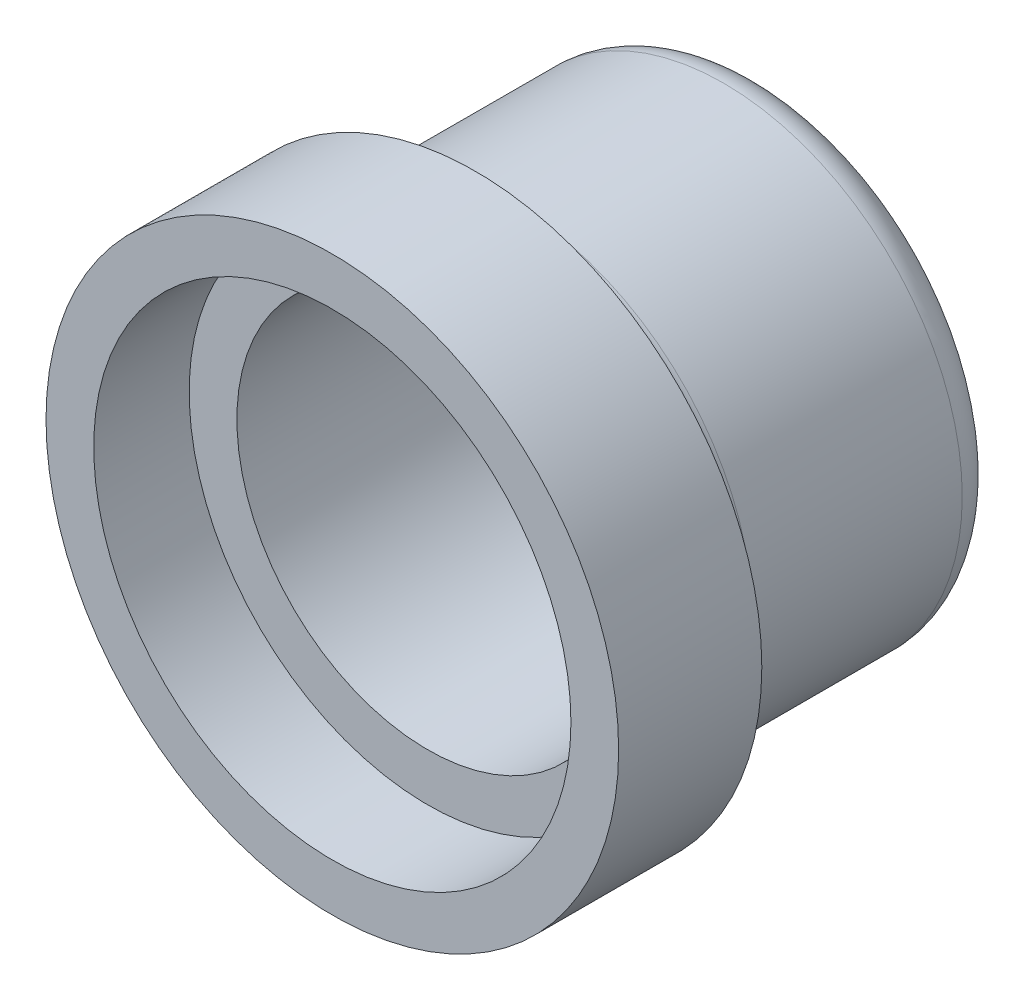
SolidWorks part; units mm, degrees
material "PVC Rígido"
ref_plane "Plano frontal" through (0, 0, 0) normal (0, 0, 1) x (1, 0, 0)
ref_plane "Plano superior" through (0, 0, 0) normal (0, 1, 0) x (1, 0, 0)
ref_plane "Plano direito" through (0, 0, 0) normal (1, 0, 0) x (0, 0, -1)
sketch "Esboço1" plane through (0, 0, 0) normal (0, 0, 1) x (1, 0, 0)
  circle A0 centre (0, 0) radius 15
  dimension "D1" = 30
extrude "Ressalto-extrusão1" add sketch "Esboço1" along normal blind 7.5 contours A0
sketch "Esboço2" plane through (0, 0, 0) normal (0, 0, -1) x (-1, 0, 0)
  circle A0 centre (0, 0) radius 12.5
  dimension "D1" = 25
extrude "Ressalto-extrusão2" add sketch "Esboço2" along normal blind 15
shell "Casca1" thickness 2.5
fillet "Filete2" radius 2 2 edges at (-12.5, 0, 0) (-12.5, 0, -15)
